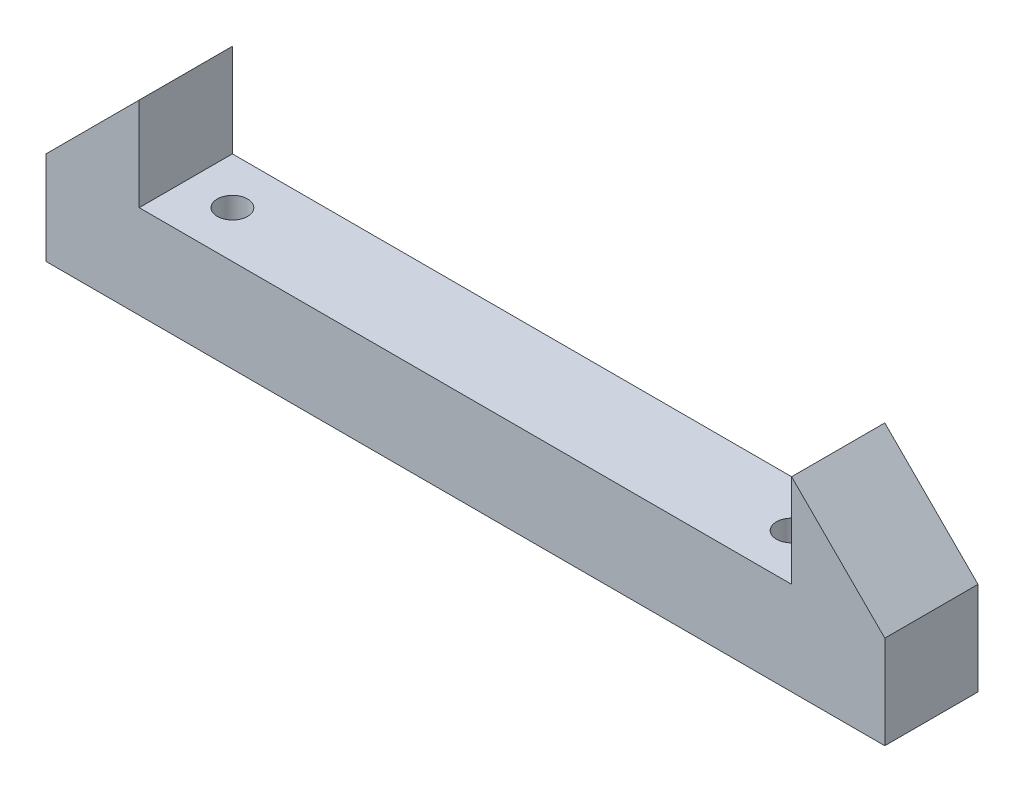
SolidWorks part; units mm, degrees
ref_plane "Front Plane" through (0, 0, 0) normal (1, 0, 0) x (0, 1, 0)
ref_plane "Top Plane" through (0, 0, 0) normal (0, 0, 1) x (0, 1, 0)
ref_plane "Right Plane" through (0, 0, 0) normal (0, 1, 0) x (-1, 0, 0)
sketch "Sketch1" plane through (0, 0, 0) normal (0, 0, 1) x (0, 1, 0)
  line L0 (-44.6403, 50.639) -> (-44.6403, -21.361)
  line L1 (-44.6403, -21.361) -> (-36.6403, -21.361)
  line L2 (-36.6403, -21.361) -> (-28.6403, -13.361)
  line L3 (-28.6403, -13.361) -> (-36.6403, -13.361)
  line L4 (-36.6403, -13.361) -> (-36.6403, 42.639)
  line L5 (-36.6403, 42.639) -> (-28.6403, 42.639)
  line L6 (-28.6403, 42.639) -> (-36.6403, 50.639)
  line L7 (-36.6403, 50.639) -> (-44.6403, 50.639)
  point P2 (-44.6403, 14.639)
  point P9 (-36.6403, 14.639)
  dimension "D1" = 56
  dimension "D2" = 72
  dimension "D3" = 8
  dimension "D4" = 8
extrude "Boss-Extrude1" add sketch "Sketch1" along normal blind 8
sketch "Sketch2" plane through (0, -36.6403, 0) normal (0, 1, 0) x (-1, 0, 0)
  line L0 (14.639, 8) -> (14.639, 0) construction
  line L1 (-13.361, 8) -> (42.639, 8) construction
  line L2 (-13.361, 0) -> (42.639, 0) construction
  line L3 (-13.361, 8) -> (-13.361, 0) construction
  circle A0 centre (-9.361, 4) radius 1.3
  circle A1 centre (38.639, 4) radius 1.3
  point P8 (14.639, 4)
  dimension "D2" = 2.6
  dimension "D1" = 4
extrude "Cut-Extrude1" cut sketch "Sketch2" against normal up to next
